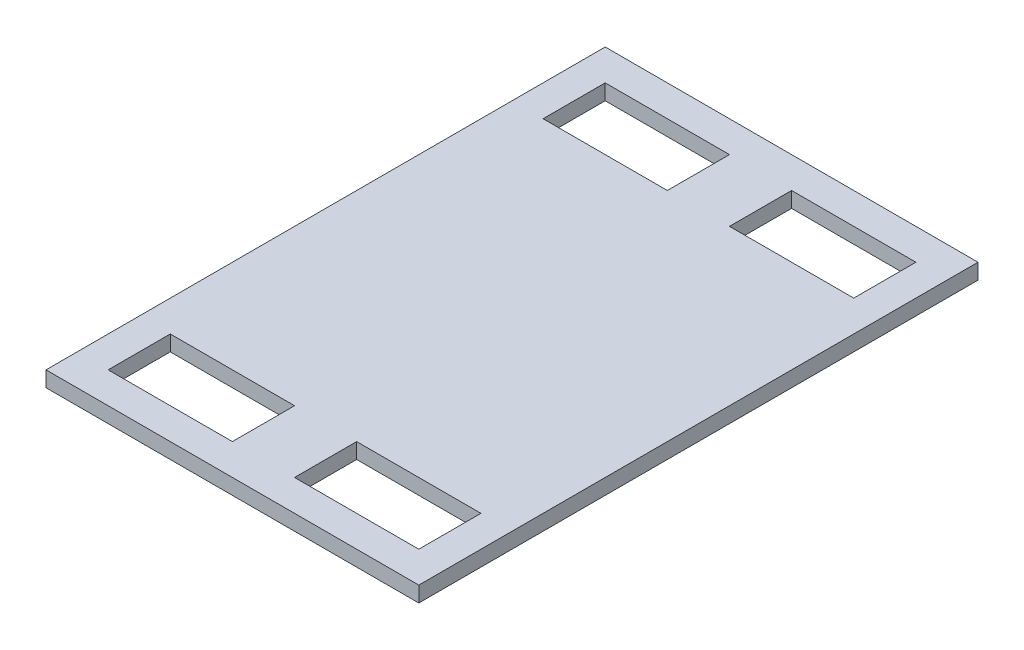
SolidWorks part; units mm, degrees
ref_plane "Front Plane" through (0, 0, 0) normal (0, 0, 1) x (1, 0, 0)
ref_plane "Top Plane" through (0, 0, 0) normal (0, 1, 0) x (1, 0, 0)
ref_plane "Right Plane" through (0, 0, 0) normal (1, 0, 0) x (0, 0, -1)
sketch "Sketch1" plane through (0, 0, 0) normal (0, 1, 0) x (1, 0, 0)
  line L1 (0, 0) -> (120, 0)
  line L2 (0, 0) -> (0, 180)
  line L3 (0, 180) -> (120, 180)
  line L4 (120, 0) -> (120, 180)
  dimension "D1" = 180
  dimension "D2" = 120
extrude "Boss-Extrude1" add sketch "Sketch1" along normal blind 5
sketch "Sketch2" plane through (0, 5, 0) normal (0, 1, 0) x (1, 0, 0)
  line L1 (0, 180) -> (0, 0) construction
  line L2 (120, 180) -> (0, 180) construction
  circle A0 centre (5, 165) radius 1.5
  circle A1 centre (5, 155) radius 1.5
  circle A2 centre (53, 155) radius 1.5
  circle A3 centre (53, 165) radius 1.5
  dimension "D1" = 3
  dimension "D3" = 10
  dimension "D4" = 5
  dimension "D2" = 15
  dimension "D5" = 48
extrude "Cut-Extrude1" [suppressed] cut sketch "Sketch2" against normal blind 5 contours A1 | A0 | A3 | A2
sketch "Sketch3" plane through (0, 0, 0) normal (0, -1, 0) x (1, 0, 0)
  line L1 (50, -150) -> (10, -150)
  line L2 (50, -150) -> (50, -170)
  line L3 (50, -170) -> (10, -170)
  line L4 (10, -150) -> (10, -170)
  line L5 (120, -180) -> (0, -180) construction
  line L6 (0, -180) -> (0, 0) construction
  dimension "D1" = 10
  dimension "D2" = 20
  dimension "D3" = 40
  dimension "D4" = 10
extrude "Cut-Extrude2" cut sketch "Sketch3" against normal up to surface (5 mm away) contours L3 L4 L1 L2 up to face at (60, 5, -90)
ref_plane "Plane1" through (60, 0, 0) normal (-1, 0, 0) x (0, 0, 1)
ref_plane "Plane2" through (0, 0, -90) normal (0, 0, -1) x (-1, 0, 0)
mirror "Mirror1" about plane through (60, 0, 0) normal (-1, 0, 0) of "Cut-Extrude1", "Cut-Extrude2"
mirror "Mirror2" about plane through (0, 0, -90) normal (0, 0, -1) of "Mirror1", "Cut-Extrude2"
